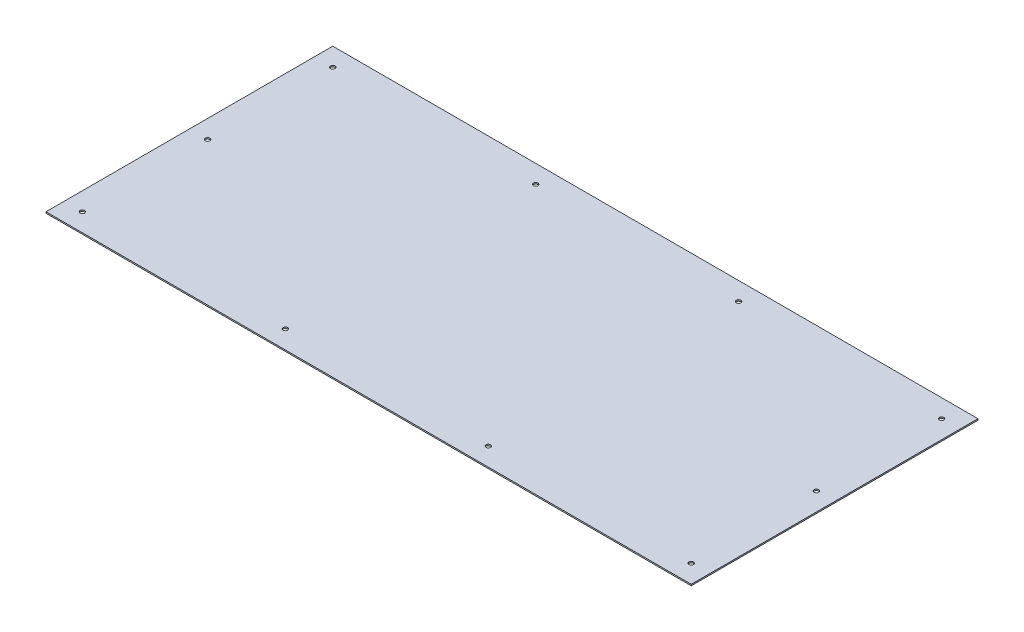
SolidWorks part; units mm, degrees
ref_plane "Alzado" through (0, 0, 0) normal (0, 0, 1) x (1, 0, 0)
ref_plane "Planta" through (0, 0, 0) normal (0, 1, 0) x (1, 0, 0)
ref_plane "Vista lateral" through (0, 0, 0) normal (1, 0, 0) x (0, 0, -1)
sketch "Croquis1" plane through (0, 0, 0) normal (0, 1, 0) x (1, 0, 0)
  line L1 (-450, 200) -> (450, 200)
  line L2 (-450, 200) -> (-450, -200)
  line L3 (-450, -200) -> (450, -200)
  line L4 (450, 200) -> (450, -200)
  line L5 (-450, 200) -> (450, -200) construction
  line L6 (-450, -200) -> (450, 200) construction
  point P0 (0, 0)
  dimension "D1" = 900
  dimension "D2" = 400
extrude "Saliente-Extruir1" add sketch "Croquis1" along normal blind 1.9
sketch "Croquis3" plane through (0, 1.9, 0) normal (0, 1, 0) x (1, 0, 0)
  line L0 (-450, -200) -> (450, -200) construction
  line L1 (424.6, -174.6) -> (-424.6, -174.6) construction
  line L2 (424.6, -174.6) -> (424.6, 174.6) construction
  line L3 (424.6, 174.6) -> (-424.6, 174.6) construction
  line L4 (-424.6, -174.6) -> (-424.6, 174.6) construction
  line L5 (424.6, -174.6) -> (-424.6, 174.6) construction
  line L6 (424.6, 174.6) -> (-424.6, -174.6) construction
  line L7 (450, -200) -> (450, 200) construction
  line L8 (0, -174.6) -> (0, 174.6) construction
  line L9 (0, 0) -> (-248.0994, 0) construction
  circle A0 centre (-424.6, -174.6) radius 3.175
  circle A1 centre (-424.6, 174.6) radius 3.175
  circle A2 centre (-424.6, 0) radius 3.175
  circle A3 centre (424.6, 174.6) radius 3.175
  circle A4 centre (424.6, 0) radius 3.175
  circle A5 centre (424.6, -174.6) radius 3.175
  circle A6 centre (-141.54, -174.6) radius 3.175
  circle A7 centre (141.52, -174.6) radius 3.175
  circle A8 centre (141.52, 174.6) radius 3.175
  circle A9 centre (-141.54, 174.6) radius 3.175
  point P0 (0, 0)
  dimension "D3" = 6.35
  dimension "D4" = 6.35
  dimension "D5" = 6.35
  dimension "D1" = 25.4
  dimension "D2" = 25.4
  dimension "D6" = 3
extrude "Cortar-Extruir1" cut sketch "Croquis3" against normal blind 10
